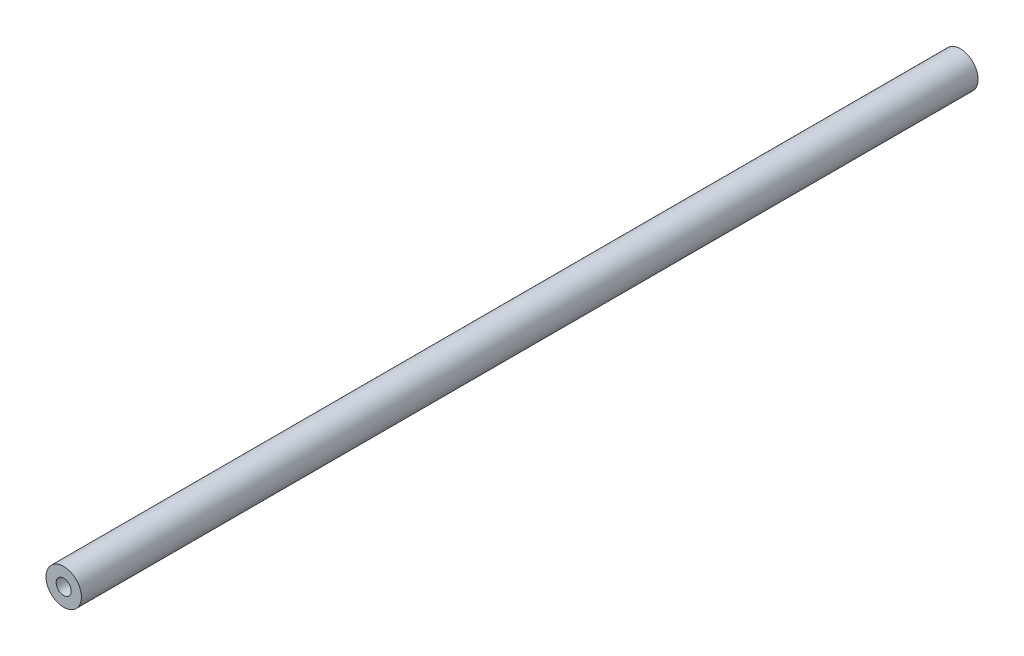
SolidWorks part; units mm, degrees
material "6061-T6 (SS)"
ref_plane "Front Plane" through (0, 0, 0) normal (0, 0, 1) x (1, 0, 0)
ref_plane "Top Plane" through (0, 0, 0) normal (0, 1, 0) x (1, 0, 0)
ref_plane "Right Plane" through (0, 0, 0) normal (1, 0, 0) x (0, 0, -1)
sketch "Sketch1" plane through (0, 0, 0) normal (0, 0, 1) x (1, 0, 0)
  circle A0 centre (0, 0) radius 4.7625
  dimension "D1" = 9.525
extrude "Boss-Extrude1" add sketch "Sketch1" along normal mid plane 241.3
hole_wizard "#10-32 Tapped Hole1" positions "3DSketch1" profile "Sketch2" tap size "#10-32" standard "ANSI Inch"
sketch3d "3DSketch1"
  line L0 (0, 0, 120.65) -> (0, 0, -120.65) construction
  point P0 (0, 0, 120.65)
  point P4 (0, 0, -120.65)
sketch "Sketch2" plane through (0, 0, 120.65) normal (1, 0, 0) x (0, -1, 0)
  line L0 (0, 0) -> (0, 13.1513)
  line L1 (0, 13.1513) -> (2.0193, 11.938)
  line L2 (2.0193, 11.938) -> (2.0193, 0)
  line L5 (2.0193, 0) -> (0, 0)
  line L10 (0, 13.1513) -> (-2.0193, 11.938) construction
  line L11 (0, -6.35) -> (0, 107.95) construction
  dimension "Tap Drill Dia." = 4.0386
  dimension "Tap Drill Depth" = 11.938
  dimension "Drill Angle" = 118
cosmetic thread "Hole Thread1" parameters "D1"=9.652, "D2"=4.826
cosmetic thread "Hole Thread2" parameters "D1"=9.652, "D2"=4.826
